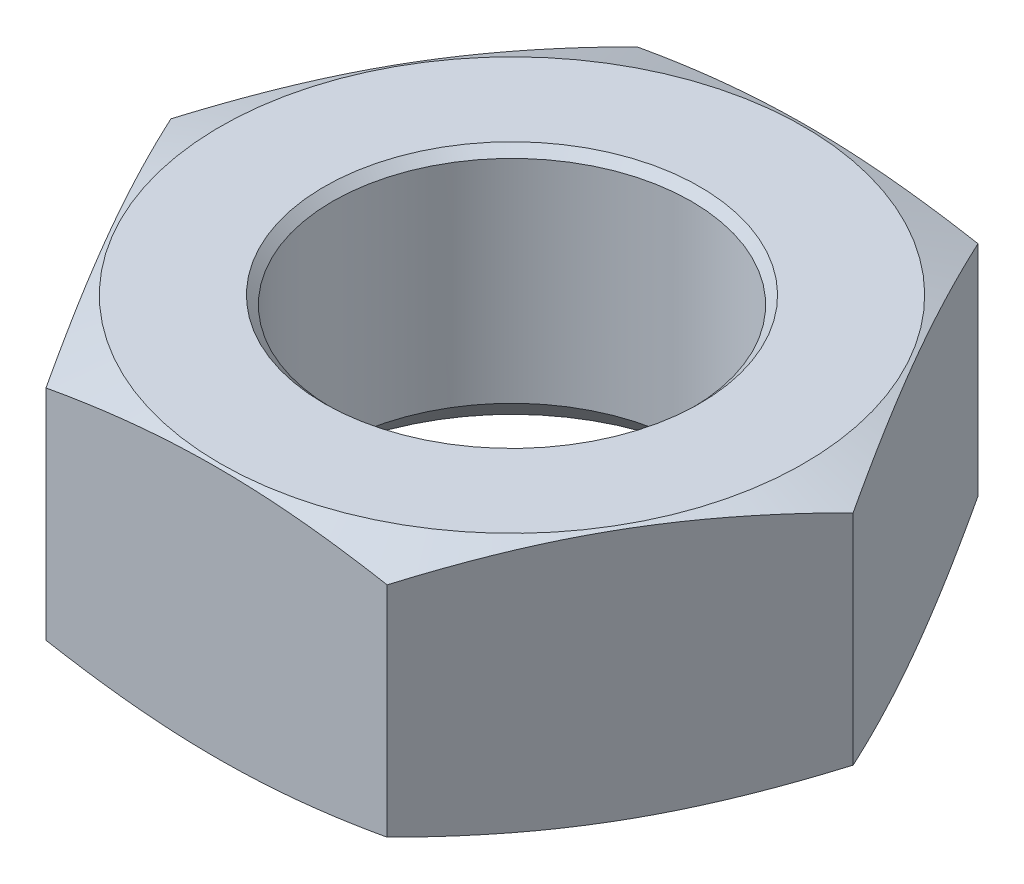
SolidWorks part; units mm, degrees
material "AISI 1020"
ref_plane "Plano superior" through (0, 0, 0) normal (0, 0, 1) x (1, 0, 0)
ref_plane "Plano frontal" through (0, 0, 0) normal (0, 1, 0) x (1, 0, 0)
ref_plane "Plano direito" through (0, 0, 0) normal (1, 0, 0) x (0, 0, -1)
sketch "Esboço1" plane through (0, 0, 0) normal (0, 1, 0) x (1, 0, 0)
  line L1 (4.0415, 7) -> (-4.0415, 7)
  line L2 (-4.0415, 7) -> (-8.0829, 0)
  line L3 (-8.0829, 0) -> (-4.0415, -7)
  line L4 (-4.0415, -7) -> (4.0415, -7)
  line L5 (4.0415, -7) -> (8.0829, 0)
  line L6 (8.0829, 0) -> (4.0415, 7)
  circle A0 centre (0, 0) radius 7 construction
  dimension "D1" = 14
extrude "Ressalto-extrusão2" add sketch "Esboço1" along normal blind 6
hole_wizard "Furo roscado de M101" positions "Esboço3" profile "Esboço4" tap size "M10" standard "DIN" end condition up to next
sketch "Esboço3" plane through (0, 0, 0) normal (0, -1, 0) x (-1, 0, 0)
  point P0 (0, 0)
sketch "Esboço4" plane through (0, 0, 0) normal (1, 0, 0) x (0, 0, -1)
  line L0 (0, 0) -> (0, 6)
  line L1 (0, 6) -> (4.25, 6)
  line L2 (4.25, 6) -> (4.25, 0.775)
  line L3 (4.25, 0.775) -> (5.025, 0)
  line L5 (5.025, 0) -> (0, 0)
  line L6 (-4.25, 0.775) -> (-5.025, 0) construction
  line L11 (0, -6.35) -> (0, 107.95) construction
  dimension "Thru Tap Drill Dia." = 8.5
  dimension "Thru Tap Drill Depth" = 6
  dimension "Near C'Sink Dia." = 10.05
  dimension "Near C'Sink Angle" = 90
cosmetic thread "Rosca de furo1" parameters "D2"=10
cosmetic thread "Representação de rosca1" parameters "D2"=10
chamfer "Chanfro2" distance 0.2 angle 45 1 edges at (0, 6, 4.25)
sketch "Esboço5" plane through (0, 6, 0) normal (0, 1, 0) x (1, 0, 0)
  circle A0 centre (0, 0) radius 6.9143
extrude "Corte-extrusão1" cut sketch "Esboço5" against normal blind 13 draft 70 flip side to cut
sketch "Esboço6" plane through (0, 0, 0) normal (0, -1, 0) x (1, 0, 0)
  circle A0 centre (0, 0) radius 6.9948
extrude "Corte-extrusão2" cut sketch "Esboço6" against normal blind 13 draft 70 flip side to cut
